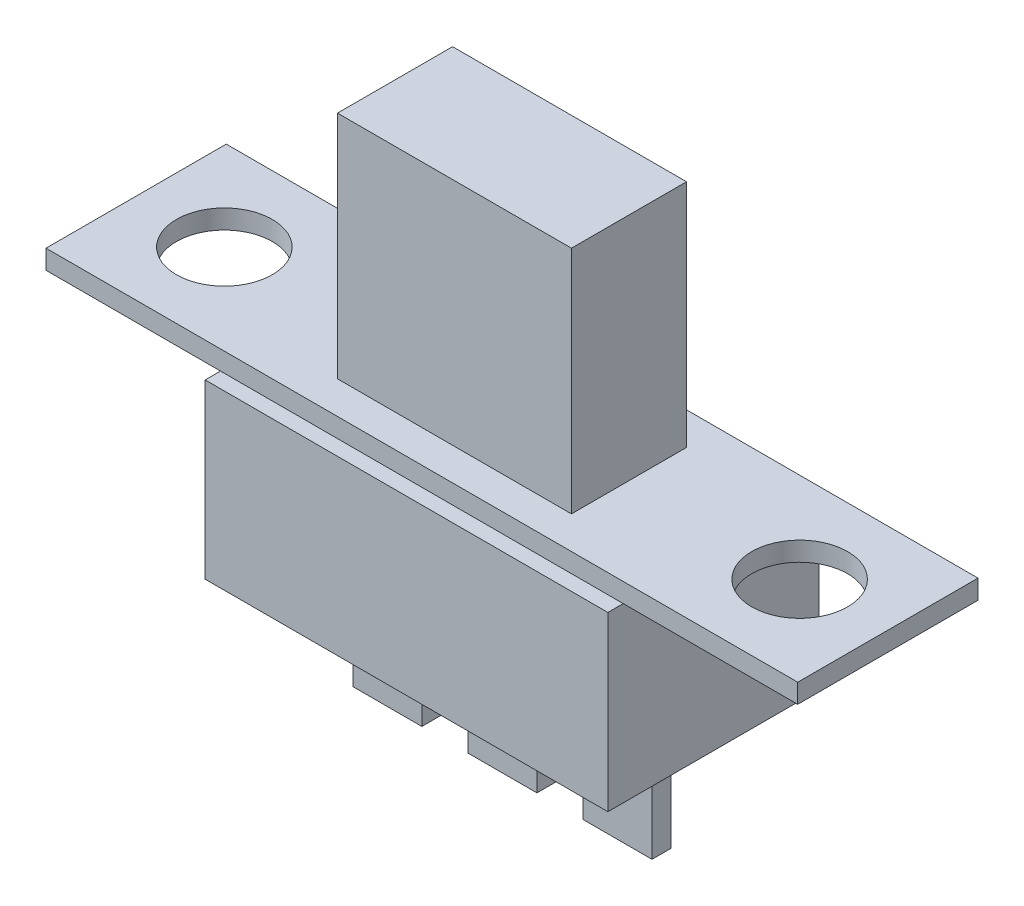
SolidWorks part; units mm, degrees
ref_plane "前视基准面" through (0, 0, 0) normal (0, 0, 1) x (1, 0, 0)
ref_plane "上视基准面" through (0, 0, 0) normal (0, 1, 0) x (1, 0, 0)
ref_plane "右视基准面" through (0, 0, 0) normal (1, 0, 0) x (0, 0, -1)
other "Configuration Table"
sketch "草图1" plane through (0, 0, 0) normal (0, 1, 0) x (1, 0, 0)
  line L1 (0, 2.35) -> (9.8, 2.35)
  line L2 (0, 2.35) -> (0, -2.35)
  line L3 (0, -2.35) -> (9.8, -2.35)
  line L4 (9.8, 2.35) -> (9.8, -2.35)
  line L5 (0, 2.35) -> (9.8, -2.35) construction
  line L6 (0, -2.35) -> (9.8, 2.35) construction
  circle A0 centre (7.5, 0) radius 1.25
  point P4 (4.9, 0)
  point P8 (0, 0)
  dimension "D3" = 7.5
  dimension "D4" = 2.5
  dimension "D1" = 9.8
  dimension "D2" = 4.7
extrude "凸台-拉伸1" add sketch "草图1" along normal blind 0.5
sketch "草图2" plane through (0, 0, 0) normal (0, -1, 0) x (1, 0, 0)
  line L1 (0, 2.75) -> (5.25, 2.75)
  line L2 (0, 2.75) -> (0, -2.75)
  line L3 (0, -2.75) -> (5.25, -2.75)
  line L4 (5.25, 2.75) -> (5.25, -2.75)
  line L5 (0, 2.75) -> (5.25, -2.75) construction
  line L6 (0, -2.75) -> (5.25, 2.75) construction
  point P4 (2.625, 0)
  dimension "D1" = 5.5
  dimension "D2" = 5.25
extrude "凸台-拉伸2" add sketch "草图2" along normal blind 4.5
sketch "草图3" plane through (0, 0, 0) normal (0, 0, 1) x (1, 0, 0)
  line L0 (5.25, -4.5) -> (0, -4.5) construction
  line L1 (2.1, -4.5) -> (3.9, -4.5)
  line L2 (2.1, -4.5) -> (2.1, -7.5)
  line L3 (2.1, -7.5) -> (3.9, -7.5)
  line L4 (3.9, -4.5) -> (3.9, -7.5)
  line L5 (2.1, -4.5) -> (3.9, -7.5) construction
  line L6 (2.1, -7.5) -> (3.9, -4.5) construction
  line L7 (0, -4.5) -> (0, 0) construction
  line L8 (0, -4.5) -> (0.9, -4.5)
  line L9 (0, -4.5) -> (0, -7.5)
  line L10 (0, -7.5) -> (0.9, -7.5)
  line L11 (0.9, -4.5) -> (0.9, -7.5)
  line L12 (0, -4.5) -> (0.9, -7.5) construction
  line L13 (0, -7.5) -> (0.9, -4.5) construction
  point P4 (3, -6)
  point P11 (0.45, -6)
  dimension "D1" = 1.8
  dimension "D2" = 3
  dimension "D3" = 3
  dimension "D4" = 0.9
extrude "凸台-拉伸3" add sketch "草图3" along normal blind 0.25 and the other way blind 0.25
mirror "镜向1" about plane through (0, 0.5, -2.35) normal (1, 0, 0) of bodies 108
sketch "草图4" plane through (0, 0.5, 0) normal (0, 1, 0) x (1, 0, 0)
  line L1 (-3.05, 1.5) -> (3.05, 1.5)
  line L2 (-3.05, 1.5) -> (-3.05, -1.5)
  line L3 (-3.05, -1.5) -> (3.05, -1.5)
  line L4 (3.05, 1.5) -> (3.05, -1.5)
  line L5 (-3.05, 1.5) -> (3.05, -1.5) construction
  line L6 (-3.05, -1.5) -> (3.05, 1.5) construction
  point P4 (0, 0)
  point P5 (0, 0)
  dimension "D1" = 3
  dimension "D2" = 6.1
extrude "凸台-拉伸4" add sketch "草图4" along normal blind 6
